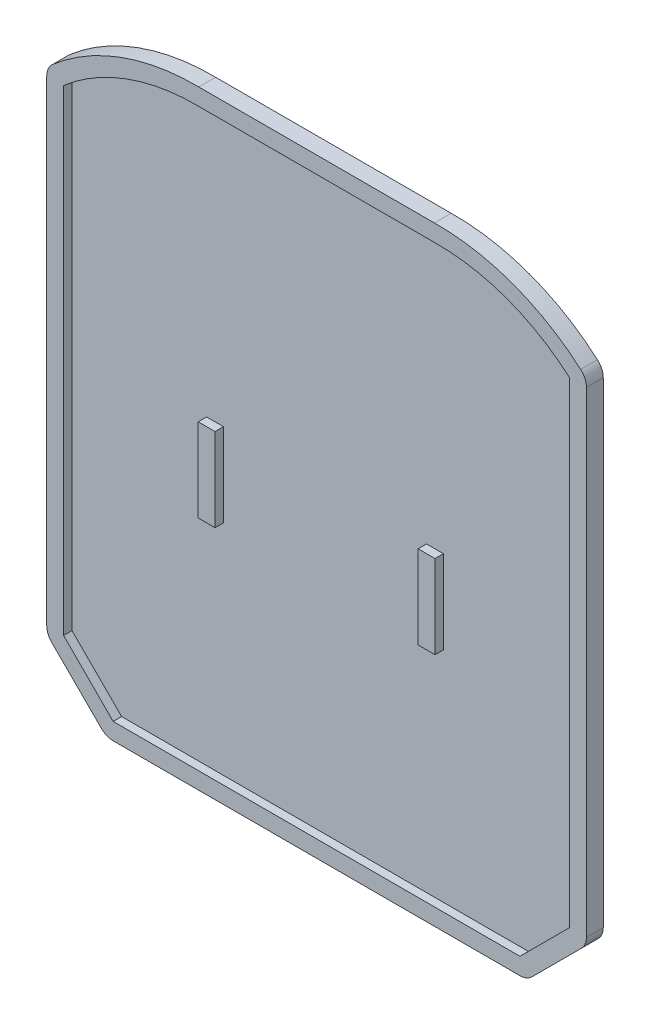
SolidWorks part; units mm, degrees
ref_plane "Front Plane" through (0, 0, 0) normal (0, 0, 1) x (1, 0, 0)
ref_plane "Top Plane" through (0, 0, 0) normal (0, 1, 0) x (1, 0, 0)
ref_plane "Right Plane" through (0, 0, 0) normal (1, 0, 0) x (0, 0, -1)
sketch "Sketch1" plane through (0, 0, 0) normal (0, 0, 1) x (1, 0, 0)
  line L0 (0, 0) -> (250, 0)
  line L2 (285.3553, 35.3553) -> (285.3553, 326.9553)
  line L6 (-35.3553, 326.9553) -> (-35.3553, 35.3553)
  line L9 (285.3553, 35.3553) -> (250, 0)
  line L10 (0, 0) -> (-35.3553, 35.3553)
  line L11 (55, 361.9553) -> (195, 361.9553)
  arc A0 (-35.3553, 326.9553) -> (55, 361.9553) centre (53.3964, 231.9652) cw
  arc A1 (285.3553, 326.9553) -> (195, 361.9553) centre (196.6036, 231.9652) ccw
  point P8 (125, 0)
  point P10 (125, 361.9553)
  dimension "D12" = 130
  dimension "D11" = 130
  dimension "D1" = 250
  dimension "D2" = 50
  dimension "D3" = 135
  dimension "D4" = 135
  dimension "D5" = 50
  dimension "D6" = 135
  dimension "D7" = 135
  dimension "D8" = 291.6
  dimension "D9" = 291.6
  dimension "D10" = 140
  dimension "D13" = 35.3553
extrude "Boss-Extrude1" add sketch "Sketch1" along normal blind 10
sketch "Sketch4" plane through (0, 0, 10) normal (0, 0, 1) x (1, 0, 0)
  line L0 (-25.3553, 39.4975) -> (4.1421, 10)
  line L1 (4.1421, 10) -> (245.8579, 10)
  line L2 (245.8579, 10) -> (275.3553, 39.4975)
  line L3 (275.3553, 39.4975) -> (275.3553, 322.5089)
  line L4 (195.0629, 351.9553) -> (54.9371, 351.9553)
  line L5 (-25.3553, 322.5089) -> (-25.3553, 39.4975)
  line L6 (-35.3553, 35.3553) -> (0, 0)
  line L7 (0, 0) -> (250, 0)
  line L8 (250, 0) -> (285.3553, 35.3553)
  line L9 (285.3553, 35.3553) -> (285.3553, 326.9553)
  line L10 (195, 361.9553) -> (55, 361.9553)
  line L11 (-35.3553, 326.9553) -> (-35.3553, 35.3553)
  line L12 (-35.3553, 35.3553) -> (0, 0)
  line L13 (0, 0) -> (250, 0)
  line L14 (250, 0) -> (285.3553, 35.3553)
  line L15 (285.3553, 35.3553) -> (285.3553, 326.9553)
  line L16 (195, 361.9553) -> (55, 361.9553)
  line L17 (-35.3553, 326.9553) -> (-35.3553, 35.3553)
  arc A0 (275.3553, 322.5089) -> (195.0629, 351.9553) centre (196.6036, 231.9652) ccw
  arc A1 (54.9371, 351.9553) -> (-25.3553, 322.5089) centre (53.3964, 231.9652) ccw
  arc A2 (285.3553, 326.9553) -> (195, 361.9553) centre (196.6036, 231.9652) ccw
  arc A3 (55, 361.9553) -> (-35.3553, 326.9553) centre (53.3964, 231.9652) ccw
  arc A4 (285.3553, 326.9553) -> (195, 361.9553) centre (196.6036, 231.9652) ccw
  arc A5 (55, 361.9553) -> (-35.3553, 326.9553) centre (53.3964, 231.9652) ccw
  dimension "D1" = 0
  dimension "D2" = 10
extrude "Cut-Extrude3" cut sketch "Sketch4" against normal blind 5 contours A1 L5 L0 L1 L2 L3 A0 L4
sketch "Sketch5" plane through (0, 0, 5) normal (0, 0, 1) x (1, 0, 0)
  line L0 (-25.3553, 322.5089) -> (-25.3553, 39.4975) construction
  line L1 (54.6447, 189.4553) -> (64.6447, 189.4553)
  line L2 (54.6447, 189.4553) -> (54.6447, 139.9553)
  line L3 (54.6447, 139.9553) -> (64.6447, 139.9553)
  line L4 (64.6447, 189.4553) -> (64.6447, 139.9553)
  line L5 (195.0629, 351.9553) -> (54.9371, 351.9553) construction
  line L6 (125, 351.9553) -> (125, 31.9023) construction
  line L7 (195.0629, 351.9553) -> (54.9371, 351.9553) construction
  line L8 (195.3553, 139.9553) -> (185.3553, 139.9553)
  line L9 (185.3553, 189.4553) -> (185.3553, 139.9553)
  line L10 (195.3553, 189.4553) -> (185.3553, 189.4553)
  line L11 (195.3553, 189.4553) -> (195.3553, 139.9553)
  dimension "D1" = 10
  dimension "D2" = 49.5
  dimension "D3" = 80
  dimension "D4" = 162.5
extrude "Boss-Extrude2" add sketch "Sketch5" along normal blind 5 contours L9 L8 L11 L10 | L2 L3 L4 L1
fillet "Fillet1" radius 10 6 edges at (285.3553, 326.9553, 5) (285.3553, 35.3553, 5) (250, 0, 5) (0, 0, 5) (-35.3553, 35.3553, 5) (-35.3553, 326.9553, 5)
sketch "Sketch6" plane through (0, 0, 0) normal (0, 0, -1) x (-1, 0, 0)
  line L1 (-235.3553, 330) -> (-225.3553, 330)
  line L2 (-235.3553, 330) -> (-235.3553, 30)
  line L3 (-235.3553, 30) -> (-225.3553, 30)
  line L4 (-225.3553, 330) -> (-225.3553, 30)
  line L10 (-285.3553, 322.5089) -> (-285.3553, 39.4975)
  line L11 (-282.4264, 32.4264) -> (-252.9289, 2.9289)
  line L12 (-245.8579, 0) -> (-4.1421, 0)
  line L13 (2.9289, 2.9289) -> (32.4264, 32.4264)
  line L14 (35.3553, 39.4975) -> (35.3553, 322.5089)
  line L15 (-55, 361.9553) -> (-195, 361.9553)
  line L16 (-285.3553, 322.5089) -> (-285.3553, 39.4975)
  line L17 (-282.4264, 32.4264) -> (-252.9289, 2.9289)
  line L18 (-245.8579, 0) -> (-4.1421, 0)
  line L19 (2.9289, 2.9289) -> (32.4264, 32.4264)
  line L20 (35.3553, 39.4975) -> (35.3553, 322.5089)
  line L21 (-55, 361.9553) -> (-195, 361.9553)
  arc A8 (-195, 361.9553) -> (-281.918, 330.0542) centre (-196.6036, 231.9652) ccw
  arc A9 (-281.918, 330.0542) -> (-285.3553, 322.5089) centre (-275.3553, 322.5089) ccw
  arc A10 (-285.3553, 39.4975) -> (-282.4264, 32.4264) centre (-275.3553, 39.4975) ccw
  arc A11 (-252.9289, 2.9289) -> (-245.8579, 0) centre (-245.8579, 10) ccw
  arc A12 (-4.1421, 0) -> (2.9289, 2.9289) centre (-4.1421, 10) ccw
  arc A13 (32.4264, 32.4264) -> (35.3553, 39.4975) centre (25.3553, 39.4975) ccw
  arc A14 (35.3553, 322.5089) -> (31.918, 330.0542) centre (25.3553, 322.5089) ccw
  arc A15 (31.918, 330.0542) -> (-55, 361.9553) centre (-53.3964, 231.9652) ccw
  arc A16 (-195, 361.9553) -> (-281.918, 330.0542) centre (-196.6036, 231.9652) ccw
  arc A17 (-281.918, 330.0542) -> (-285.3553, 322.5089) centre (-275.3553, 322.5089) ccw
  arc A18 (-285.3553, 39.4975) -> (-282.4264, 32.4264) centre (-275.3553, 39.4975) ccw
  arc A19 (-252.9289, 2.9289) -> (-245.8579, 0) centre (-245.8579, 10) ccw
  arc A20 (-4.1421, 0) -> (2.9289, 2.9289) centre (-4.1421, 10) ccw
  arc A21 (32.4264, 32.4264) -> (35.3553, 39.4975) centre (25.3553, 39.4975) ccw
  arc A22 (35.3553, 322.5089) -> (31.918, 330.0542) centre (25.3553, 322.5089) ccw
  arc A23 (31.918, 330.0542) -> (-55, 361.9553) centre (-53.3964, 231.9652) ccw
  dimension "D1" = 10
  dimension "D2" = 300
  dimension "D4" = 30
  dimension "D5" = 50
  dimension "D3" = 0
extrude "Cut-Extrude5" cut sketch "Sketch6" against normal blind 4 contours L2 L3 L4 L1
sketch "Sketch8" plane through (0, 0, 4) normal (0, 0, -1) x (-1, 0, 0)
  line L0 (-235.3553, 330) -> (-235.3553, 30) construction
  line L1 (-235.3553, 300) -> (-225.3553, 300)
  line L2 (-235.3553, 300) -> (-235.3553, 270)
  line L3 (-235.3553, 270) -> (-225.3553, 270)
  line L4 (-225.3553, 300) -> (-225.3553, 270)
  line L5 (-225.3553, 330) -> (-225.3553, 30) construction
  line L6 (-225.3553, 180) -> (-235.3553, 180) construction
  line L7 (-225.3553, 330) -> (-225.3553, 30) construction
  line L8 (-235.3553, 90) -> (-225.3553, 90)
  line L9 (-225.3553, 60) -> (-225.3553, 90)
  line L10 (-235.3553, 60) -> (-225.3553, 60)
  line L11 (-235.3553, 60) -> (-235.3553, 90)
  line L12 (-235.3553, 330) -> (-225.3553, 330) construction
  dimension "D1" = 30
  dimension "D2" = 30
extrude "Boss-Extrude3" add sketch "Sketch8" along normal blind 4
sketch "Sketch10" plane through (0, 0, 0) normal (0, 0, -1) x (-1, 0, 0)
  line L2 (-125, 361.9553) -> (-125, 32.4264)
  line L3 (-24.6447, 30) -> (-24.6447, 330)
  line L4 (-225.3553, 330) -> (-235.3553, 330)
  line L5 (-225.3553, 30) -> (-225.3553, 330)
  line L6 (-235.3553, 30) -> (-225.3553, 30)
  line L7 (-235.3553, 330) -> (-235.3553, 30)
  line L8 (-225.3553, 330) -> (-235.3553, 330)
  line L9 (-225.3553, 30) -> (-225.3553, 330)
  line L10 (-235.3553, 30) -> (-225.3553, 30)
  line L11 (-235.3553, 330) -> (-235.3553, 30)
  line L12 (-14.6447, 30) -> (-24.6447, 30)
  line L13 (-14.6447, 330) -> (-14.6447, 30)
  line L14 (-55, 361.9553) -> (-195, 361.9553)
  line L15 (-285.3553, 322.5089) -> (-285.3553, 39.4975)
  line L16 (-282.4264, 32.4264) -> (-252.9289, 2.9289)
  line L17 (-245.8579, 0) -> (-4.1421, 0)
  line L18 (2.9289, 2.9289) -> (32.4264, 32.4264)
  line L19 (35.3553, 39.4975) -> (35.3553, 322.5089)
  line L20 (-55, 361.9553) -> (-195, 361.9553)
  line L21 (-285.3553, 322.5089) -> (-285.3553, 39.4975)
  line L22 (-282.4264, 32.4264) -> (-252.9289, 2.9289)
  line L23 (-245.8579, 0) -> (-4.1421, 0)
  line L24 (2.9289, 2.9289) -> (32.4264, 32.4264)
  line L25 (35.3553, 39.4975) -> (35.3553, 322.5089)
  line L26 (-24.6447, 330) -> (-14.6447, 330)
  arc A8 (-195, 361.9553) -> (-281.918, 330.0542) centre (-196.6036, 231.9652) ccw
  arc A9 (-281.918, 330.0542) -> (-285.3553, 322.5089) centre (-275.3553, 322.5089) ccw
  arc A10 (-285.3553, 39.4975) -> (-282.4264, 32.4264) centre (-275.3553, 39.4975) ccw
  arc A11 (-252.9289, 2.9289) -> (-245.8579, 0) centre (-245.8579, 10) ccw
  arc A12 (-4.1421, 0) -> (2.9289, 2.9289) centre (-4.1421, 10) ccw
  arc A13 (32.4264, 32.4264) -> (35.3553, 39.4975) centre (25.3553, 39.4975) ccw
  arc A14 (35.3553, 322.5089) -> (31.918, 330.0542) centre (25.3553, 322.5089) ccw
  arc A15 (31.918, 330.0542) -> (-55, 361.9553) centre (-53.3964, 231.9652) ccw
  arc A16 (-195, 361.9553) -> (-281.918, 330.0542) centre (-196.6036, 231.9652) ccw
  arc A17 (-281.918, 330.0542) -> (-285.3553, 322.5089) centre (-275.3553, 322.5089) ccw
  arc A18 (-285.3553, 39.4975) -> (-282.4264, 32.4264) centre (-275.3553, 39.4975) ccw
  arc A19 (-252.9289, 2.9289) -> (-245.8579, 0) centre (-245.8579, 10) ccw
  arc A20 (-4.1421, 0) -> (2.9289, 2.9289) centre (-4.1421, 10) ccw
  arc A21 (32.4264, 32.4264) -> (35.3553, 39.4975) centre (25.3553, 39.4975) ccw
  arc A22 (35.3553, 322.5089) -> (31.918, 330.0542) centre (25.3553, 322.5089) ccw
  arc A23 (31.918, 330.0542) -> (-55, 361.9553) centre (-53.3964, 231.9652) ccw
  dimension "D1" = 0
  dimension "D2" = 0
extrude "Cut-Extrude6" cut sketch "Sketch10" against normal blind 4 contours L3 L26 L13 L12
sketch "Sketch11" plane through (0, 0, 4) normal (0, 0, -1) x (-1, 0, 0)
  line L0 (-125, 0) -> (-125, 330.0542) construction
  line L1 (-14.6447, 90) -> (-14.6447, 60)
  line L2 (-14.6447, 60) -> (-24.6447, 60)
  line L3 (-24.6447, 60) -> (-24.6447, 90)
  line L4 (-225.3553, 90) -> (-235.3553, 90)
  line L5 (-225.3553, 60) -> (-225.3553, 90)
  line L6 (-235.3553, 60) -> (-225.3553, 60)
  line L7 (-235.3553, 90) -> (-235.3553, 60)
  line L8 (-225.3553, 90) -> (-235.3553, 90)
  line L9 (-225.3553, 60) -> (-225.3553, 90)
  line L10 (-235.3553, 60) -> (-225.3553, 60)
  line L11 (-235.3553, 90) -> (-235.3553, 60)
  line L12 (-225.3553, 300) -> (-235.3553, 300)
  line L13 (-225.3553, 270) -> (-225.3553, 300)
  line L14 (-235.3553, 270) -> (-225.3553, 270)
  line L15 (-235.3553, 300) -> (-235.3553, 270)
  line L16 (-225.3553, 300) -> (-235.3553, 300)
  line L17 (-225.3553, 270) -> (-225.3553, 300)
  line L18 (-235.3553, 270) -> (-225.3553, 270)
  line L19 (-235.3553, 300) -> (-235.3553, 270)
  line L20 (-24.6447, 90) -> (-14.6447, 90)
  line L21 (-14.6447, 270) -> (-24.6447, 270)
  line L22 (-285.3553, 322.5089) -> (-285.3553, 39.4975)
  line L23 (-282.4264, 32.4264) -> (-252.9289, 2.9289)
  line L24 (-245.8579, 0) -> (-4.1421, 0)
  line L25 (2.9289, 2.9289) -> (32.4264, 32.4264)
  line L26 (35.3553, 39.4975) -> (35.3553, 322.5089)
  line L27 (-55, 361.9553) -> (-195, 361.9553)
  line L28 (-285.3553, 322.5089) -> (-285.3553, 39.4975)
  line L29 (-282.4264, 32.4264) -> (-252.9289, 2.9289)
  line L30 (-245.8579, 0) -> (-4.1421, 0)
  line L31 (2.9289, 2.9289) -> (32.4264, 32.4264)
  line L32 (35.3553, 39.4975) -> (35.3553, 322.5089)
  line L33 (-55, 361.9553) -> (-195, 361.9553)
  line L34 (-24.6447, 270) -> (-24.6447, 300)
  line L35 (-14.6447, 300) -> (-14.6447, 270)
  line L36 (-24.6447, 300) -> (-14.6447, 300)
  arc A8 (-195, 361.9553) -> (-281.918, 330.0542) centre (-196.6036, 231.9652) ccw
  arc A9 (-281.918, 330.0542) -> (-285.3553, 322.5089) centre (-275.3553, 322.5089) ccw
  arc A10 (-285.3553, 39.4975) -> (-282.4264, 32.4264) centre (-275.3553, 39.4975) ccw
  arc A11 (-252.9289, 2.9289) -> (-245.8579, 0) centre (-245.8579, 10) ccw
  arc A12 (-4.1421, 0) -> (2.9289, 2.9289) centre (-4.1421, 10) ccw
  arc A13 (32.4264, 32.4264) -> (35.3553, 39.4975) centre (25.3553, 39.4975) ccw
  arc A14 (35.3553, 322.5089) -> (31.918, 330.0542) centre (25.3553, 322.5089) ccw
  arc A15 (31.918, 330.0542) -> (-55, 361.9553) centre (-53.3964, 231.9652) ccw
  arc A16 (-195, 361.9553) -> (-281.918, 330.0542) centre (-196.6036, 231.9652) ccw
  arc A17 (-281.918, 330.0542) -> (-285.3553, 322.5089) centre (-275.3553, 322.5089) ccw
  arc A18 (-285.3553, 39.4975) -> (-282.4264, 32.4264) centre (-275.3553, 39.4975) ccw
  arc A19 (-252.9289, 2.9289) -> (-245.8579, 0) centre (-245.8579, 10) ccw
  arc A20 (-4.1421, 0) -> (2.9289, 2.9289) centre (-4.1421, 10) ccw
  arc A21 (32.4264, 32.4264) -> (35.3553, 39.4975) centre (25.3553, 39.4975) ccw
  arc A22 (35.3553, 322.5089) -> (31.918, 330.0542) centre (25.3553, 322.5089) ccw
  arc A23 (31.918, 330.0542) -> (-55, 361.9553) centre (-53.3964, 231.9652) ccw
  dimension "D1" = 0
  dimension "D2" = 0
  dimension "D3" = 0
extrude "Boss-Extrude4" add sketch "Sketch11" along normal blind 4 contours L20 L1 L2 L3 | L36 L35 L21 L34
